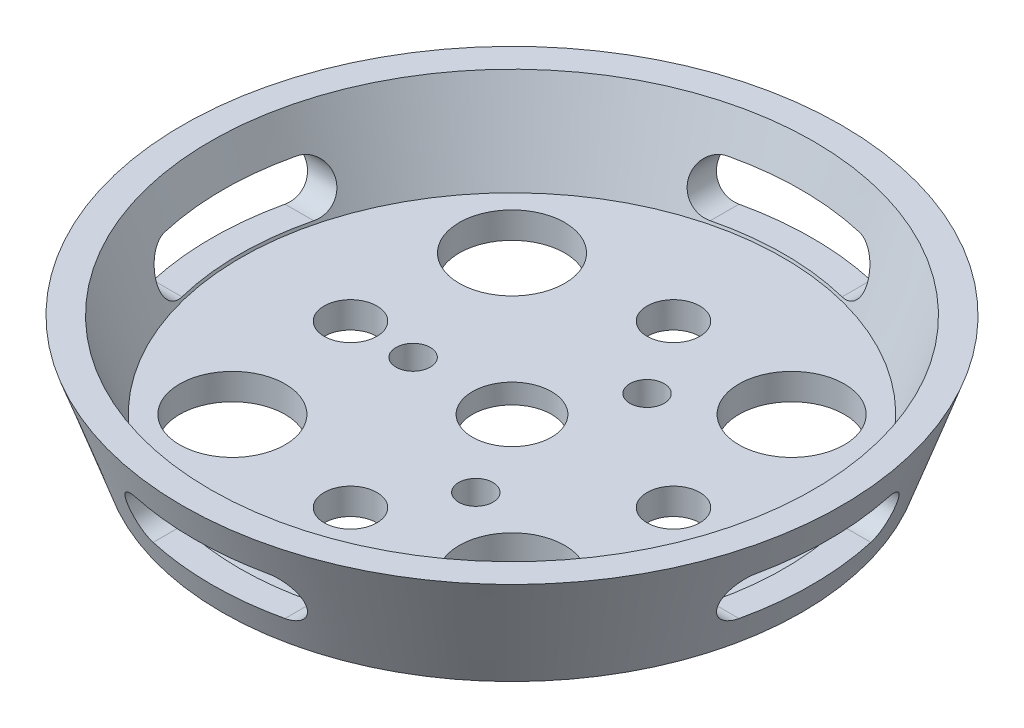
SolidWorks part; units mm, degrees
ref_plane "Front Plane" through (0, 0, 0) normal (0, 0, 1) x (1, 0, 0)
ref_plane "Top Plane" through (0, 0, 0) normal (0, 1, 0) x (1, 0, 0)
ref_plane "Right Plane" through (0, 0, 0) normal (1, 0, 0) x (0, 0, -1)
sketch "Sketch1" plane through (0, 0, 0) normal (0, 1, 0) x (1, 0, 0)
  circle A0 centre (0, 0) radius 22
  dimension "D1" = 44
ref_plane "Plane1" through (0, 8.5, 0) normal (0, 1, 0) x (1, 0, 0)
sketch "Sketch2" plane through (0, 8.5, 0) normal (0, 1, 0) x (1, 0, 0)
  circle A0 centre (0, 0) radius 25
  dimension "D1" = 50
loft "Loft1" add profiles "Sketch2", "Sketch1"
shell "Shell1" thickness 2
sketch "Sketch3" plane through (0, 0, 0) normal (0, -1, 0) x (1, 0, 0)
  line L0 (0, 0) -> (-10.6066, -10.6066) construction
  line L1 (0, 0) -> (-12.25, 0) construction
  circle A0 centre (0, 0) radius 3
  circle A1 centre (0, 0) radius 12.25 construction
  circle A2 centre (0, -12.25) radius 2
  circle A3 centre (-12.25, 0) radius 2
  circle A4 centre (0, 12.25) radius 2
  circle A5 centre (12.25, 0) radius 2
  circle A10 centre (0, 0) radius 15 construction
  circle A11 centre (-10.6066, -10.6066) radius 4
  circle A12 centre (-10.6066, 10.6066) radius 4
  circle A13 centre (10.6066, 10.6066) radius 4
  circle A14 centre (10.6066, -10.6066) radius 4
  circle A15 centre (0, 0) radius 7.5 construction
  circle A16 centre (-7.5, 0) radius 1.3
  circle A17 centre (3.75, 6.4952) radius 1.3
  circle A18 centre (3.75, -6.4952) radius 1.3
  point P15 (0, 0)
  point P24 (0, 0)
  point P26 (0, 0)
  point P33 (0, 0)
  point P34 (-0.4791, 2.9615)
  dimension "D1" = 6
  dimension "D2" = 24.5
  dimension "D3" = 4
  dimension "D6" = 45
  dimension "D8" = 30
  dimension "D10" = 10.6066
  dimension "D7" = 8
  dimension "D12" = 15
  dimension "D13" = 2.6
  dimension "D5" = 12.25
  dimension "D11" = 15
  dimension "D15" = 7.5
  dimension "D16" = 6.4952
  dimension "D4" = 4
  dimension "D9" = 4
  dimension "D14" = 3
extrude "Cut-Extrude1" cut sketch "Sketch3" against normal through all
sketch "Sketch4" plane through (0, 0, 0) normal (0, 0, 1) x (1, 0, 0)
  line L0 (5, 4) -> (-5, 4) construction
  line L1 (5, 2.2) -> (-5, 2.2)
  line L2 (5, 5.8) -> (-5, 5.8)
  arc A0 (5, 2.2) -> (5, 5.8) centre (5, 4) ccw
  arc A1 (-5, 5.8) -> (-5, 2.2) centre (-5, 4) ccw
  point P2 (0, 4)
  dimension "D2" = 1.8
  dimension "D1" = 10
  dimension "D3" = 4
extrude "Cut-Extrude2" cut sketch "Sketch4" along normal blind 31
pattern_circular "CirPattern1" count 4 over 360 about axis through (0, 0, 0) along (0, 1, 0) of "Cut-Extrude2"
sketch "Sketch5" plane through (0, 0, 0) normal (0, -1, 0) x (1, 0, 0)
  circle A0 centre (0, 0) radius 5
  dimension "D1" = 10
extrude "Cut-Extrude3" cut sketch "Sketch5" against normal blind 0.5
